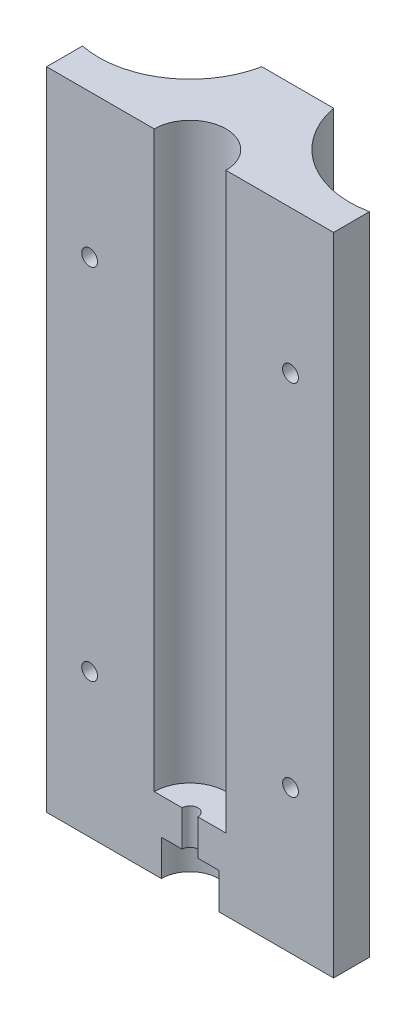
SolidWorks part; units mm, degrees
ref_plane "Ebene vorne" through (0, 0, 0) normal (0, 0, 1) x (1, 0, 0)
ref_plane "Ebene oben" through (0, 0, 0) normal (0, 1, 0) x (1, 0, 0)
ref_plane "Ebene rechts" through (0, 0, 0) normal (1, 0, 0) x (0, 0, -1)
sketch "Skizze2" plane through (0, 0, 0) normal (0, 1, 0) x (1, 0, 0)
  line L1 (0, 0) -> (40, 0)
  line L2 (0, 0) -> (0, 15)
  line L3 (0, 15) -> (40, 15)
  line L4 (40, 0) -> (40, 15)
  dimension "D1" = 40
  dimension "D2" = 15
extrude "Aufsatz-Linear austragen1" add sketch "Skizze2" along normal blind 90 contours L2 L3 L4 L1
sketch "Skizze3" plane through (0, 90, 0) normal (0, 1, 0) x (1, 0, 0)
  line L0 (0, 0) -> (40, 0) construction
  line L1 (0, -55) -> (0, 55) construction
  circle A0 centre (20, 0) radius 5
  dimension "D1" = 20
extrude "Schnitt-Linear austragen1" cut sketch "Skizze3" against normal blind 80
sketch "Skizze4" plane through (0, 0, 0) normal (0, -1, 0) x (1, 0, 0)
  circle A0 centre (20, 0) radius 4
  point P2 (0, 0)
  dimension "D1" = 20
  dimension "D2" = 8
extrude "Schnitt-Linear austragen2" cut sketch "Skizze4" against normal blind 5
sketch "Skizze5" plane through (0, 10, 0) normal (0, 1, 0) x (1, 0, 0)
  line L0 (15, 0) -> (25, 0) construction
  circle A0 centre (20, 0) radius 1.1
extrude "Schnitt-Linear austragen3" cut sketch "Skizze5" against normal through all
hole_wizard "Stirnsenkung für M2 Flachkopfschraube mit Schlitz1" positions "Skizze7" profile "Skizze8" counterbore size "M2" standard "DIN" end condition through all
sketch "Skizze7" plane through (0, 0, -15) normal (0, 0, -1) x (-1, 0, 0)
  line L0 (0, 90) -> (-40, 90) construction
  line L1 (8.25, 0) -> (-8.25, 0) construction
  line L2 (0, 8.25) -> (0, -8.25) construction
  line L3 (-40, 90) -> (-40, 0) construction
  point P0 (-6, 70)
  point P2 (-6, 20)
  point P4 (-34, 20)
  point P6 (-34, 70)
  dimension "D1" = 20
  dimension "D2" = 20
  dimension "D3" = 20
  dimension "D4" = 20
  dimension "D5" = 6
  dimension "D6" = 6
  dimension "D7" = 6
  dimension "D8" = 6
sketch "Skizze8" plane through (6, 70, -15) normal (1, 0, 0) x (0, 1, 0)
  line L0 (0, 0) -> (0, 15)
  line L1 (0, 15) -> (1.1, 15)
  line L3 (1.1, 15) -> (1.1, 12.6)
  line L4 (2.5, 12.6) -> (1.1, 12.6)
  line L5 (2.5, 12.6) -> (2.5, 1)
  line L6 (2.5, 1) -> (3.5, 0)
  line L7 (3.5, 0) -> (0, 0)
  line L8 (-2.5, 1) -> (-3.5, 0) construction
  line L11 (0, -6.35) -> (0, 107.95) construction
  dimension "Bohrerdurchmesser" = 2.2
  dimension "Bohrungstiefe" = 15
  dimension "Senkdurchmesser2" = 5
  dimension "Senktiefe2" = 12.6
  dimension "Senkdurchmesser4 (Oben)" = 7
  dimension "Senkwinkel2 (Oben)" = 90
sketch "Skizze11" plane through (0, 90, 0) normal (0, 1, 0) x (1, 0, 0)
  line L0 (40, 0) -> (40, 15) construction
  line L1 (0, 15) -> (40, 15) construction
  arc A0 (40, 5) -> (25, 15) centre (37.5, 17.5) cw
  dimension "D1" = 5
  dimension "D2" = 15
extrude "Schnitt-Linear austragen6" cut sketch "Skizze11" against normal through all and the other way through all flip side to cut
sketch "Skizze14" plane through (0, 90, 0) normal (0, 1, 0) x (1, 0, 0)
  line L2 (0, 15) -> (25, 15) construction
  line L3 (0, -8.25) -> (0, 8.25) construction
  arc A0 (15, 15) -> (0, 5) centre (2.5, 17.5) cw
  point P3 (0, 0)
  dimension "D1" = 15
  dimension "D2" = 5
extrude "Schnitt-Linear austragen7" cut sketch "Skizze14" against normal through all and the other way through all flip side to cut
